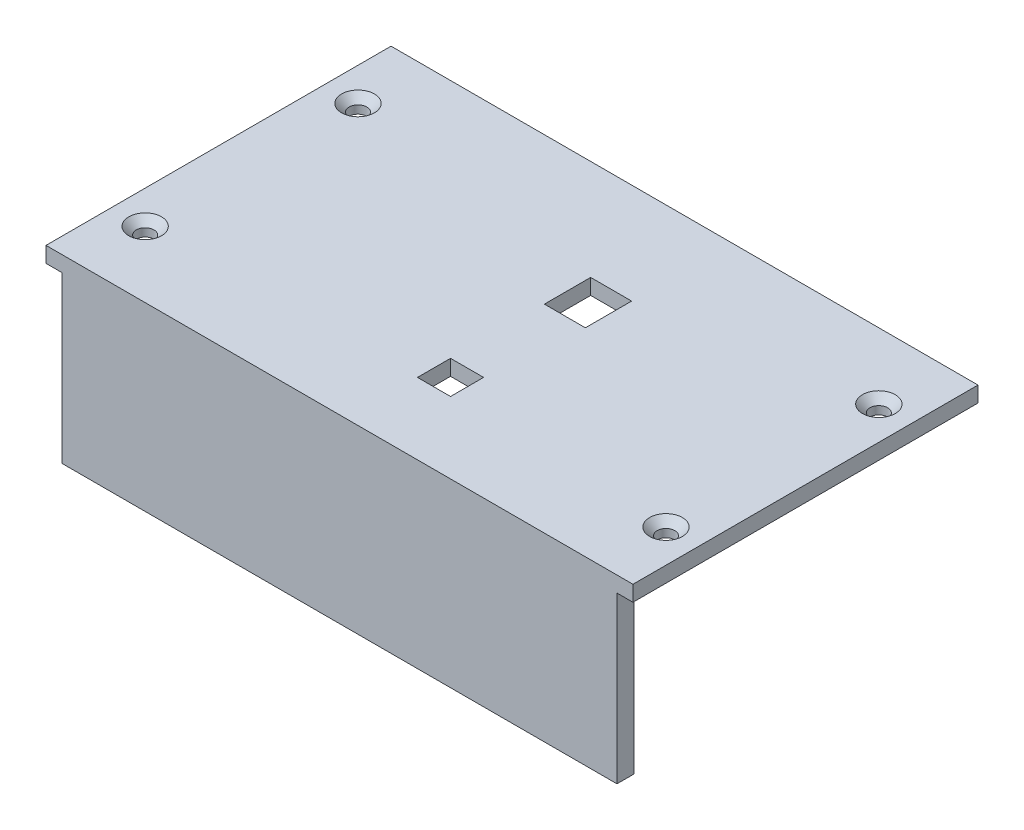
SolidWorks part; units mm, degrees
material "ABS"
ref_plane "Front Plane" through (0, 0, 0) normal (0, 0, 1) x (1, 0, 0)
ref_plane "Top Plane" through (0, 0, 0) normal (0, 1, 0) x (1, 0, 0)
ref_plane "Right Plane" through (0, 0, 0) normal (1, 0, 0) x (0, 0, -1)
sketch "Sketch1" plane through (0, 0, 0) normal (0, 1, 0) x (1, 0, 0)
  line L1 (-56.388, -33.147) -> (56.388, -33.147)
  line L2 (-56.388, -33.147) -> (-56.388, 33.147)
  line L3 (-56.388, 33.147) -> (56.388, 33.147)
  line L4 (56.388, -33.147) -> (56.388, 33.147)
  line L5 (-56.388, -33.147) -> (56.388, 33.147) construction
  line L6 (-56.388, 33.147) -> (56.388, -33.147) construction
  point P0 (0, 0)
  dimension "D1" = 66.294
  dimension "D2" = 112.776
extrude "Boss-Extrude1" add sketch "Sketch1" along normal blind 3 contours L2 L3 L4 L1
sketch "Sketch2" plane through (0, 3, 0) normal (0, 1, 0) x (1, 0, 0)
  line L0 (-56.388, 33.147) -> (56.388, 33.147) construction
  line L1 (-56.388, -33.147) -> (-56.388, 33.147) construction
  line L2 (56.388, -33.147) -> (56.388, 33.147) construction
  line L3 (-56.388, -33.147) -> (56.388, -33.147) construction
  point P0 (-50.038, 20.447)
  point P1 (-50.038, -20.447)
  point P2 (50.038, -20.447)
  point P3 (50.038, 20.447)
  dimension "D1" = 12.7
  dimension "D2" = 6.35
  dimension "D3" = 6.35
  dimension "D4" = 12.7
  dimension "D5" = 12.7
  dimension "D6" = 6.35
  dimension "D7" = 6.35
  dimension "D8" = 12.7
hole_wizard "CSK for M3 Countersunk Flat Head Screw1" positions "3DSketch1" profile "Sketch3" countersink size "M3" standard "ISO" end condition up to next
sketch3d "3DSketch1"
  point P0 (-50.038, 3, -20.447)
  point P3 (-50.038, 3, 20.447)
  point P6 (50.038, 3, 20.447)
  point P9 (50.038, 3, -20.447)
sketch "Sketch3" plane through (-50.038, 3, -20.447) normal (1, 0, 0) x (0, 0, 1)
  line L0 (0, 0) -> (0, 3)
  line L1 (0, 3) -> (1.7, 3)
  line L2 (1.7, 3) -> (1.7, 1.45)
  line L3 (1.7, 1.45) -> (3.15, 0)
  line L5 (3.15, 0) -> (0, 0)
  line L6 (-1.7, 1.45) -> (-3.15, 0) construction
  line L11 (0, -6.35) -> (0, 107.95) construction
  dimension "Thru Hole Dia." = 3.4
  dimension "Thru Hole Depth" = 3
  dimension "Near C'Sink Dia." = 6.3
  dimension "Near C'Sink Angle" = 90
sketch "Sketch4" plane through (0, 0, 0) normal (0, -1, 0) x (1, 0, 0)
  line L1 (-53.3146, 33.147) -> (53.3146, 33.147)
  line L2 (-53.3146, 33.147) -> (-53.3146, 29.845)
  line L3 (-53.3146, 29.845) -> (53.3146, 29.845)
  line L4 (53.3146, 33.147) -> (53.3146, 29.845)
  line L5 (-56.388, 33.147) -> (-56.388, -33.147) construction
  line L6 (56.388, 33.147) -> (56.388, -33.147) construction
  line L7 (-56.388, 33.147) -> (56.388, 33.147) construction
  point P7 (-51.5286, 29.8356)
  dimension "D1" = 3.302
  dimension "D2" = 3.0734
  dimension "D3" = 3.0734
extrude "Boss-Extrude2" add sketch "Sketch4" along normal blind 31.75 contours L3 L4 L1 L2
sketch "Sketch6" plane through (0, 3, 0) normal (0, 1, 0) x (1, 0, 0)
  line L0 (-56.388, -33.147) -> (-56.388, 33.147) construction
  line L1 (1.27, -13.081) -> (7.62, -13.081)
  line L2 (1.27, -13.081) -> (1.27, -19.431)
  line L3 (1.27, -19.431) -> (7.62, -19.431)
  line L4 (7.62, -13.081) -> (7.62, -19.431)
  line L5 (-56.388, 33.147) -> (56.388, 33.147) construction
  line L6 (-56.388, -33.147) -> (56.388, -33.147) construction
  line L7 (1.27, 13.843) -> (9.144, 13.843)
  line L8 (1.27, 13.843) -> (1.27, 4.953)
  line L9 (1.27, 4.953) -> (9.144, 4.953)
  line L10 (9.144, 13.843) -> (9.144, 4.953)
  dimension "D1" = 6.35
  dimension "D2" = 6.35
  dimension "D3" = 57.658
  dimension "D4" = 46.228
  dimension "D5" = 7.874
  dimension "D6" = 8.89
  dimension "D7" = 38.1
extrude "Cut-Extrude1" cut sketch "Sketch6" against normal up to next
